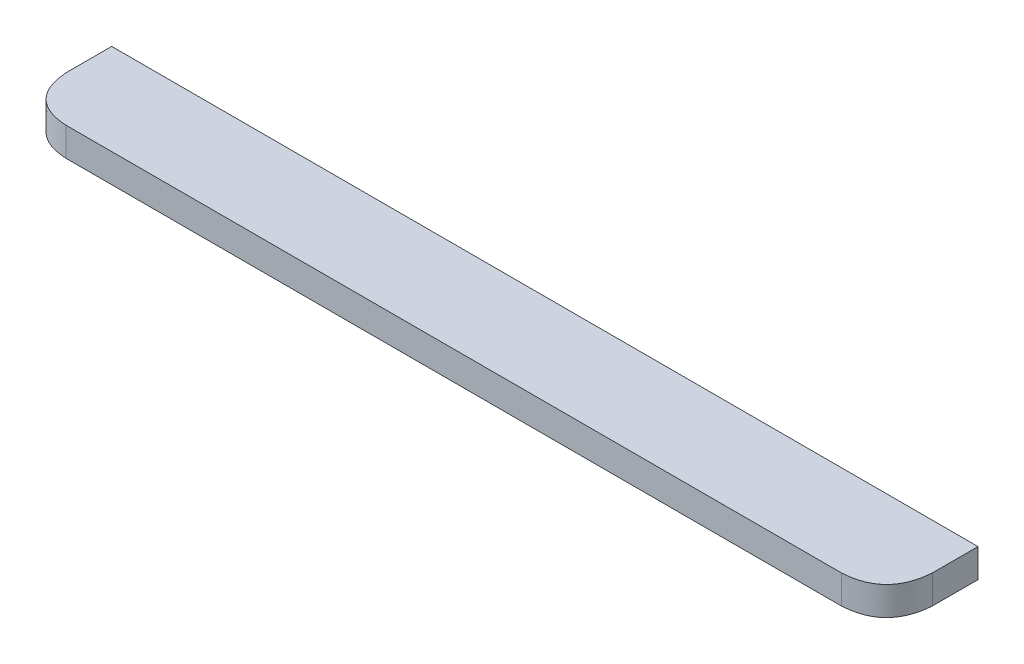
SolidWorks part; units mm, degrees
ref_plane "Front Plane" through (0, 0, 0) normal (0, 0, 1) x (1, 0, 0)
ref_plane "Top Plane" through (0, 0, 0) normal (0, 1, 0) x (1, 0, 0)
ref_plane "Right Plane" through (0, 0, 0) normal (1, 0, 0) x (0, 0, -1)
sketch "Sketch2" plane through (0, 0, 0) normal (0, 1, 0) x (1, 0, 0)
  line L0 (0, 0) -> (0, -25.0342) construction
  line L1 (-108.077, -25.0342) -> (108.077, -25.0342)
  line L5 (0, 0) -> (0, 12.7) construction
  line L7 (108.077, -25.0342) -> (108.077, -12.3342) construction
  line L8 (108.077, -12.3342) -> (116.8559, -21.8599) construction
  line L9 (108.077, -12.3342) -> (120.777, -12.3342) construction
  line L11 (-108.077, -12.3342) -> (-120.777, -12.3342) construction
  line L13 (-108.077, -12.3342) -> (-116.8559, -21.8599) construction
  line L14 (-108.077, -25.0342) -> (-108.077, -12.3342) construction
  line L17 (-120.777, -12.3342) -> (-120.777, 0.3658)
  line L18 (120.777, -12.3342) -> (120.777, 0.3658)
  line L19 (120.777, 0.3658) -> (-120.777, 0.3658)
  spline S0 degree 2 poles (108.077, -25.0342) (119.9228, -24.4246) (120.777, -12.3342) knots 0 0 0 1 1 1
  spline S1 degree 2 poles (-108.077, -25.0342) (-119.9228, -24.4246) (-120.777, -12.3342) knots 0 0 0 1 1 1
  point P0 (0, 0)
  dimension "D1" = 25.4
  dimension "D2" = 12.7
  dimension "D3" = 12.7
  dimension "D4" = 12.954
  dimension "D5" = 12.7
  dimension "D6" = 12.7
  dimension "D7" = 12.7
  dimension "D8" = 12.954
  dimension "D9" = 12.7
  dimension "D10" = 241.554
extrude "Boss-Extrude1" add sketch "Sketch2" along normal blind 8
